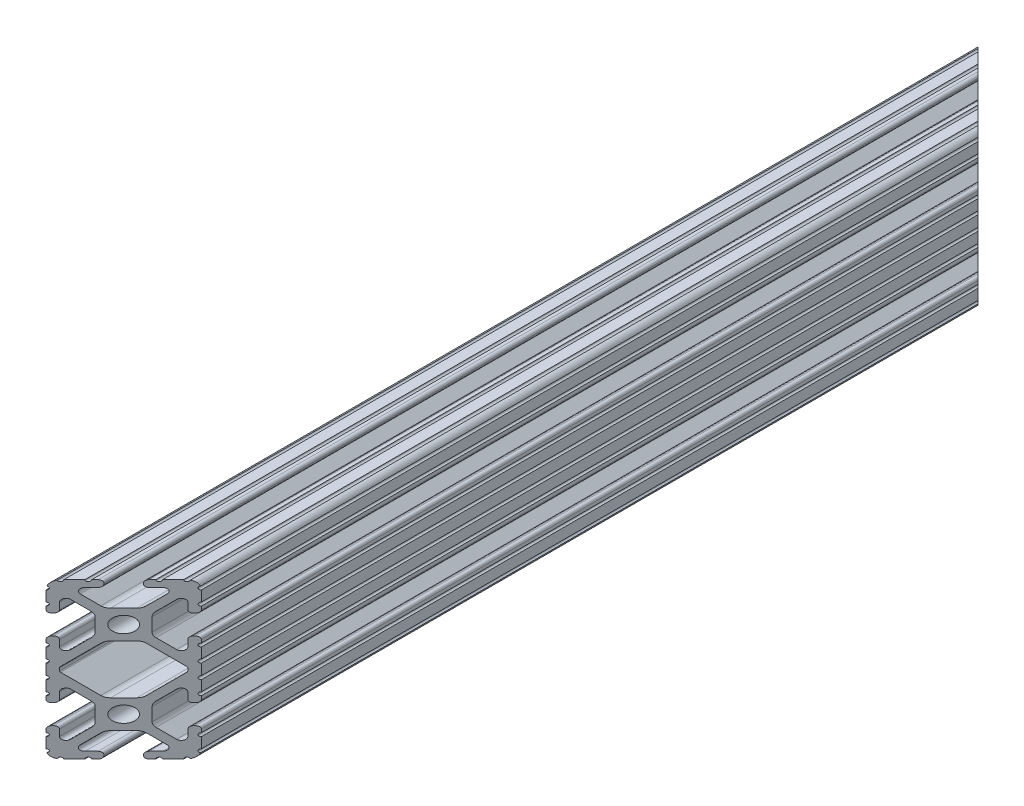
SolidWorks part; units mm, degrees
ref_plane "Front Plane" through (0, 0, 0) normal (0, 0, 1) x (1, 0, 0)
ref_plane "Top Plane" through (0, 0, 0) normal (0, 1, 0) x (1, 0, 0)
ref_plane "Right Plane" through (0, 0, 0) normal (1, 0, 0) x (0, 0, -1)
sketch "Sketch2" plane through (0, 0, 0) normal (0, 0, 1) x (1, 0, 0)
  line L0 (0, 25.4) -> (0, -25.4) construction
  line L1 (-12.7, 0) -> (12.7, 0) construction
  line L2 (3.2512, -25.4) -> (12.7, -25.4)
  line L3 (12.7, -25.4) -> (12.7, -15.9512)
  line L4 (3.2512, -25.4) -> (3.2512, -23.1902)
  line L5 (3.2512, -23.1902) -> (8.9276, -23.1902)
  line L6 (8.9276, -23.1902) -> (3.0856, -17.3482)
  line L7 (0, -12.7) -> (12.7, -25.4) construction
  line L8 (12.7, -15.9512) -> (10.4902, -15.9512)
  line L9 (10.4902, -15.9512) -> (10.4902, -21.6276)
  line L10 (10.4902, -21.6276) -> (4.6482, -15.7856)
  circle A0 centre (0, -12.7) radius 2.6035
  arc A1 (6.3485, -23.1902) -> (7.1039, -21.3665) centre (6.3485, -22.1219) ccw construction
  point P8 (0, -17.3482)
  dimension "Center Hole Diameter" = 5.207
  dimension "Rail Height" = 50.8
  dimension "Rail Width" = 25.4
  dimension "T-Slot Width" = 6.5024
  dimension "Slot Inner Width" = 14.8336
  dimension "Thickness" = 2.2098
  dimension "Slot Depth" = 5.842
  dimension "D1" = 2.2098
  dimension "C to C" = 25.4
sketch "Sketch3" plane through (0, 0, 0) normal (1, 0, 0) x (0, 0, -1)
  line L0 (-152.4, -25.4) -> (152.4, -25.4) construction
  line L1 (-127, 0) -> (127, 0) construction
  dimension "Length" = 304.8
  dimension "D1" = 25.4
sketch "Sketch4" plane through (0, 0, 0) normal (0, 0, 1) x (1, 0, 0)
  line L0 (4.1904, -25.4) -> (10.1173, -25.4)
  line L1 (3.2512, -25.4) -> (12.7, -25.4) construction
  line L2 (3.2512, -25.4) -> (3.2512, -23.1902) construction
  line L3 (3.2512, -23.1902) -> (8.9276, -23.1902) construction
  line L4 (3.2512, -24.1294) -> (3.2512, -24.4608)
  line L5 (4.1904, -23.1902) -> (6.3485, -23.1902)
  line L6 (0, -17.3482) -> (2.164, -17.3482)
  line L7 (8.9276, -23.1902) -> (3.0856, -17.3482) construction
  line L8 (3.7373, -17.9999) -> (7.1039, -21.3665)
  line L9 (12.7, -25.4) -> (12.7, -15.9512) construction
  line L10 (10.4902, -21.6276) -> (4.6482, -15.7856) construction
  line L11 (10.4902, -15.9512) -> (10.4902, -21.6276) construction
  line L12 (10.4902, -19.0485) -> (10.4902, -16.8904)
  line L13 (12.7, -15.9512) -> (10.4902, -15.9512) construction
  line L14 (11.4294, -15.9512) -> (11.7608, -15.9512)
  line L15 (12.7, -16.8904) -> (12.7, -22.8173)
  line L16 (8.6665, -19.8039) -> (5.2999, -16.4373)
  line L17 (4.6482, -12.7) -> (4.6482, -14.864)
  line L19 (0, -17.3482) -> (0, -15.3035)
  line L20 (0, 25.4) -> (0, -25.4) construction
  line L21 (4.6482, -12.7) -> (2.6035, -12.7)
  arc A0 (3.2512, -24.4608) -> (4.1904, -25.4) centre (4.1904, -24.4608) ccw
  circle A1 centre (0, -12.7) radius 2.6035 construction
  arc A2 (3.2512, -24.1294) -> (4.1904, -23.1902) centre (4.1904, -24.1294) cw
  arc A3 (6.3485, -23.1902) -> (7.1039, -21.3665) centre (6.3485, -22.1219) ccw
  arc A4 (2.164, -17.3482) -> (3.7373, -17.9999) centre (2.164, -19.5732) cw
  arc A5 (10.1173, -25.4) -> (12.7, -22.8173) centre (10.1173, -22.8173) ccw
  arc A6 (8.6665, -19.8039) -> (10.4902, -19.0485) centre (9.4219, -19.0485) ccw
  arc A7 (10.4902, -16.8904) -> (11.4294, -15.9512) centre (11.4294, -16.8904) cw
  arc A8 (11.7608, -15.9512) -> (12.7, -16.8904) centre (11.7608, -16.8904) cw
  arc A9 (5.2999, -16.4373) -> (4.6482, -14.864) centre (6.8732, -14.864) cw
  arc A11 (0, -15.3035) -> (2.6035, -12.7) centre (0, -12.7) ccw
  dimension "D1" = 2.5827
  dimension "D2" = 2.225
  dimension "D3" = 0.9392
extrude "Boss-Extrude1" add sketch "Sketch4" along normal mid plane 304.8
sketch "Sketch5" plane through (0, 0, 0) normal (0, 0, 1) x (1, 0, 0)
  line L0 (3.2512, -25.4) -> (12.7, -25.4) construction
  line L1 (4.1904, -23.1902) -> (6.3485, -23.1902) construction
  line L3 (0, -12.7) -> (12.7, -25.4) construction
  line L4 (6.3485, -23.1902) -> (6.3485, -25.4) construction
  line L5 (8.9276, -23.1902) -> (3.0856, -17.3482) construction
  circle A0 centre (10.3562, -25.4) radius 0.5524
  circle A1 centre (5.796, -25.4) radius 0.5524
  circle A2 centre (12.7, -23.0562) radius 0.5524
  circle A3 centre (12.7, -18.496) radius 0.5524
  point P10 (5.2694, -23.1902)
  point P12 (9.4219, -19.0485)
  dimension "D1" = 1.1049
extrude "Cut-Extrude1" cut sketch "Sketch5" against normal through all both and the other way through all
mirror "Mirror1" about plane through (4.6482, -12.7, 152.4) normal (0, -1, 0) of bodies 137 134
sketch "Sketch6" plane through (0, 0, 0) normal (0, 0, 1) x (1, 0, 0)
  line L0 (12.7, -1.7914) -> (12.7, 0)
  line L1 (12.7, 0) -> (9.8037, 0)
  line L2 (-12.7, 0) -> (12.7, 0) construction
  line L3 (9.8037, 0) -> (9.8037, -2.3438)
  line L4 (9.8037, -2.3438) -> (12.1476, -2.3438)
  circle A0 centre (12.7, -2.3438) radius 0.5524 construction
  arc A1 (12.7, -1.7914) -> (12.1476, -2.3438) centre (12.7, -2.3438) ccw
  arc A4 (12.58, -1.8046) -> (12.7, -2.8963) centre (12.7, -2.3438) ccw construction
  arc A6 (9.8037, 0) -> (10.8954, -0.12) centre (10.3562, 0) ccw construction
extrude "Boss-Extrude2" add sketch "Sketch6" along normal mid plane 304.8
sketch "Sketch7" plane through (0, 0, 0) normal (0, 0, 1) x (1, 0, 0)
  line L0 (5.4206, -5.7168) -> (10.3284, -0.809)
  line L1 (3.7373, -7.4001) -> (7.1039, -4.0335) construction
  line L2 (10.4902, -0.4184) -> (10.4902, 0)
  line L3 (0, 0) -> (10.4902, 0)
  line L4 (-12.7, 0) -> (12.7, 0) construction
  line L5 (0, 0) -> (5.4206, -5.7168)
  arc A0 (10.3284, -0.809) -> (10.4902, -0.4184) centre (9.9377, -0.4184) ccw
  arc A3 (12.7, -1.7914) -> (12.7, -2.8963) centre (12.7, -2.3438) ccw construction
extrude "Cut-Extrude2" cut sketch "Sketch7" against normal through all both and the other way through all
mirror "Mirror2" about plane through (0, 0, 0) normal (0, 1, 0) of bodies 139 135
mirror "Mirror3" about plane through (0, 0, 0) normal (1, 0, 0) of bodies 136
sketch "Sketch9" plane through (0, -25.4, 0) normal (0, -1, 0) x (1, 0, 0)
  line L0 (-12.7, 152.4) -> (12.7, 127)
  line L1 (12.7, 152.4) -> (12.7, -152.4) construction
  line L2 (12.7, 127) -> (12.7, 152.4)
  line L3 (12.7, 152.4) -> (-12.7, 152.4)
  line L4 (12.7, -152.4) -> (-12.7, -152.4)
  line L5 (-12.7, -152.4) -> (12.7, -127)
  line L6 (12.7, -127) -> (12.7, -152.4)
  dimension "D1" = 45
  dimension "D2" = 45
extrude "Cut-Extrude4" cut sketch "Sketch9" against normal through all
equation "\"D1@Boss-Extrude1\"=\"Length@Sketch3\""
equation "\"D1@Sketch2\"=\"Thickness@Sketch2\""
equation "\"D2@Sketch4\"=\"Slot Inner Width@Sketch2\"*0.15"
equation "\"D1@Sketch4\"=\"D3@Sketch4\"*2.75"
equation "\"D3@Sketch4\"=\"Thickness@Sketch2\"*0.425"
equation "\"D1@Sketch5\"=\"Thickness@Sketch2\"*0.5"
equation "\"D1@Boss-Extrude2\"=\"Length@Sketch3\""
